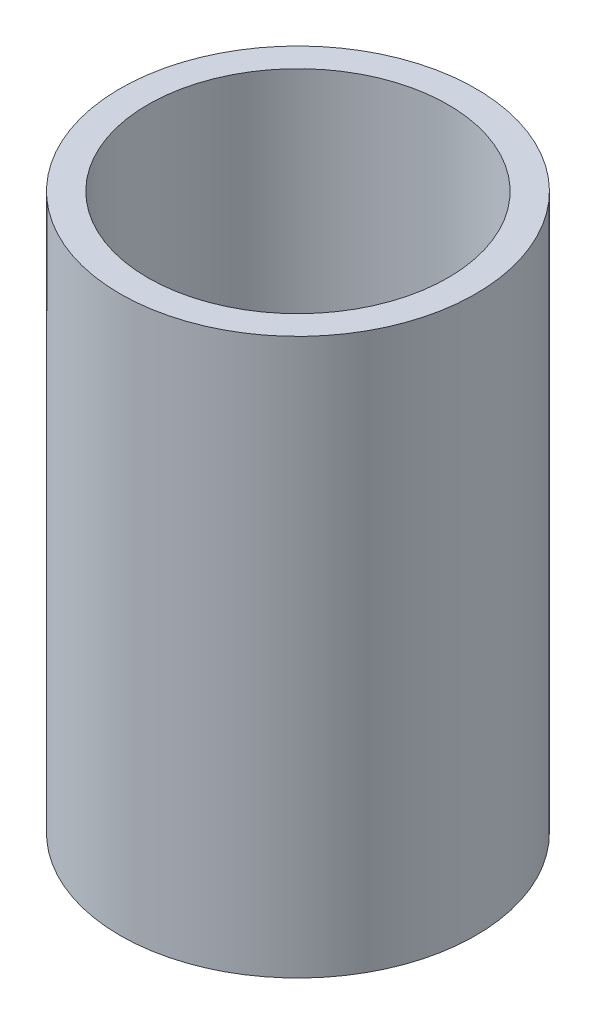
SolidWorks part; units mm, degrees
ref_plane "Front Plane" through (0, 0, 0) normal (0, 0, 1) x (1, 0, 0)
ref_plane "Top Plane" through (0, 0, 0) normal (0, 1, 0) x (1, 0, 0)
ref_plane "Right Plane" through (0, 0, 0) normal (1, 0, 0) x (0, 0, -1)
sketch "Sketch1" plane through (0, 0, 0) normal (0, 1, 0) x (1, 0, 0)
  circle A0 centre (0, 0) radius 32
  dimension "D1" = 64
extrude "Boss-Extrude1" add sketch "Sketch1" along normal blind 100
sketch "Sketch2" plane through (0, 100, 0) normal (0, 1, 0) x (1, 0, 0)
  circle A0 centre (0, 0) radius 27
  dimension "D1" = 54
extrude "Cut-Extrude1" cut sketch "Sketch2" against normal blind 85
sketch "Sketch3" plane through (0, 0, 0) normal (0, -1, 0) x (1, 0, 0)
  line L1 (-14, 14) -> (14, 14)
  line L2 (-14, 14) -> (-14, -14)
  line L3 (-14, -14) -> (14, -14)
  line L4 (14, 14) -> (14, -14)
  line L5 (-14, 14) -> (14, -14) construction
  line L6 (-14, -14) -> (14, 14) construction
  point P0 (0, 0)
  dimension "D1" = 28
  dimension "D2" = 28
extrude "Cut-Extrude2" cut sketch "Sketch3" against normal blind 25
